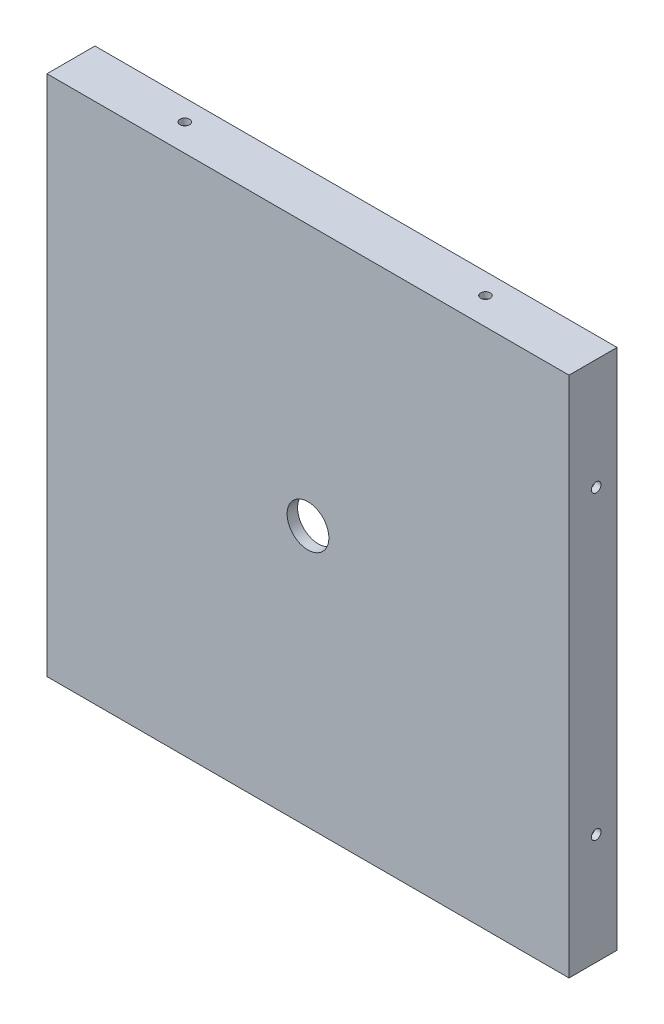
SolidWorks part; units mm, degrees
ref_plane "정면" through (0, 0, 0) normal (0, 0, 1) x (1, 0, 0)
ref_plane "윗면" through (0, 0, 0) normal (0, 1, 0) x (1, 0, 0)
ref_plane "우측면" through (0, 0, 0) normal (1, 0, 0) x (0, 0, -1)
sketch "스케치1" plane through (0, 0, 0) normal (0, 0, 1) x (1, 0, 0)
  line L1 (-125, 125) -> (125, 125)
  line L2 (-125, 125) -> (-125, -125)
  line L3 (-125, -125) -> (125, -125)
  line L4 (125, 125) -> (125, -125)
  line L5 (-125, 125) -> (125, -125) construction
  line L6 (-125, -125) -> (125, 125) construction
  circle A0 centre (0, 0) radius 10
  point P0 (0, 0)
  dimension "D1" = 250
  dimension "D2" = 250
extrude "보스-돌출1" add sketch "스케치1" along normal blind 5
sketch "스케치2" plane through (0, 0, 0) normal (0, 0, -1) x (-1, 0, 0)
  line L0 (-125, -27.4401) -> (125, -27.4401) construction
  line L1 (-125, -125) -> (-125, 125) construction
  line L2 (125, 125) -> (125, -125) construction
  text T0 "bottom\r\n"
sketch "스케치3" plane through (0, 0, 0) normal (0, 0, -1) x (-1, 0, 0)
  line L1 (-122, 122) -> (122, 122)
  line L2 (-122, 122) -> (-122, -122)
  line L3 (-122, -122) -> (122, -122)
  line L4 (122, 122) -> (122, -122)
  line L5 (-122, 122) -> (122, -122) construction
  line L6 (-122, -122) -> (122, 122) construction
  line L7 (-125, 125) -> (125, 125)
  line L8 (-125, 125) -> (-125, -125)
  line L9 (-125, -125) -> (125, -125)
  line L10 (125, 125) -> (125, -125)
  line L11 (-125, 125) -> (125, -125) construction
  line L12 (-125, -125) -> (125, 125) construction
  point P0 (0, 0)
  point P6 (0, 0)
  dimension "D1" = 3
  dimension "D2" = 3
extrude "보스-돌출2" add sketch "스케치3" along normal blind 18
hole_wizard "M4 여유 구멍1" positions "스케치4" profile "스케치6" hole size "M4" standard "KS"
sketch "스케치4" plane through (122, 0, 0) normal (-1, 0, 0) x (0, 0, 1)
  line L0 (-18, 122) -> (0, 122) construction
  line L1 (-18, -122) -> (0, -122) construction
  line L2 (-18, 122) -> (-18, -122) construction
  point P0 (-8, 72)
  point P2 (-8, -72)
  dimension "D1" = 50
  dimension "D2" = 50
  dimension "D3" = 10
  dimension "D4" = 10
sketch "스케치6" plane through (122, 72, -8) normal (0, 1, 0) x (0, 0, 1)
  line L0 (0, 0) -> (0, 3)
  line L1 (0, 3) -> (2.3, 3)
  line L2 (2.3, 3) -> (2.3, 0)
  line L5 (2.3, 0) -> (0, 0)
  line L11 (0, -6.35) -> (0, 107.95) construction
  dimension "관통 구멍 지름" = 4.6
  dimension "관통 구멍 깊이" = 3
pattern_circular "원형 패턴1" count 4 every 90 about axis through (0, 0, 0) along (0, 0, 1) of "M4 여유 구멍1"
